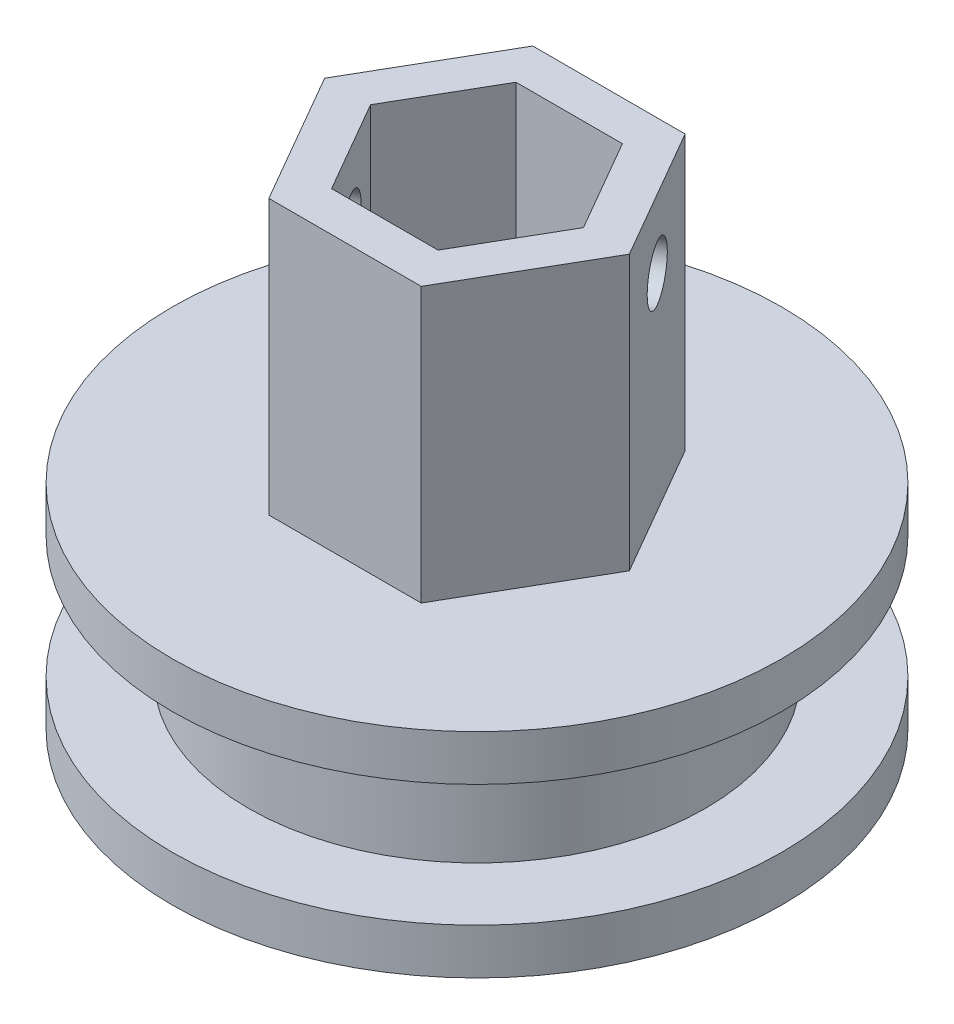
SolidWorks part; units mm, degrees
ref_plane "前视基准面" through (0, 0, 0) normal (0, 0, 1) x (1, 0, 0)
ref_plane "上视基准面" through (0, 0, 0) normal (0, 1, 0) x (1, 0, 0)
ref_plane "右视基准面" through (0, 0, 0) normal (1, 0, 0) x (0, 0, -1)
other "Configuration Table"
sketch "草图1" plane through (0, 0, 0) normal (0, 1, 0) x (1, 0, 0)
  line L1 (6.9859, 0) -> (3.493, 6.05)
  line L2 (3.493, 6.05) -> (-3.493, 6.05)
  line L3 (-3.493, 6.05) -> (-6.9859, 0)
  line L4 (-6.9859, 0) -> (-3.493, -6.05)
  line L5 (-3.493, -6.05) -> (3.493, -6.05)
  line L6 (3.493, -6.05) -> (6.9859, 0)
  line L7 (10, 0) -> (5, 8.6603)
  line L8 (5, 8.6603) -> (-5, 8.6603)
  line L9 (-5, 8.6603) -> (-10, 0)
  line L10 (-10, 0) -> (-5, -8.6603)
  line L11 (-5, -8.6603) -> (5, -8.6603)
  line L12 (5, -8.6603) -> (10, 0)
  circle A0 centre (0, 0) radius 6.05 construction
  circle A1 centre (0, 0) radius 8.6603 construction
  point P1 (5.2395, -3.025)
  dimension "D1" = 6.05
  dimension "D2" = 6.05
  dimension "D3" = 10
  dimension "D4" = 8.6603
extrude "凸台-拉伸3" add sketch "草图1" against normal blind 18
sketch "草图2" plane through (7.5, 0, -4.3301) normal (0.866, 0, -0.5) x (-0.5, 0, -0.866)
  line L2 (-5, -18) -> (-5, 0) construction
  line L3 (-5, 0) -> (5, 0) construction
  circle A0 centre (0, -4.5) radius 1.8
  dimension "D1" = 3.6
  dimension "D2" = 5
  dimension "D3" = 4.5
extrude "切除-拉伸1" cut sketch "草图2" against normal blind 17.325
sketch "草图4" plane through (0, -18, 0) normal (0, -1, 0) x (1, 0, 0)
  circle A0 centre (0, 0) radius 1.75
  circle A1 centre (0, 0) radius 20
extrude "凸台-拉伸4" add sketch "草图4" along normal blind 3
sketch "草图5" plane through (0, -21, 0) normal (0, -1, 0) x (1, 0, 0)
  circle A0 centre (0, 0) radius 1.75
  circle A1 centre (0, 0) radius 15
extrude "凸台-拉伸5" add sketch "草图5" along normal blind 8
sketch "草图6" plane through (0, -29, 0) normal (0, -1, 0) x (1, 0, 0)
  circle A0 centre (0, 0) radius 1.75
  circle A1 centre (0, 0) radius 20
extrude "凸台-拉伸6" add sketch "草图6" along normal blind 3
